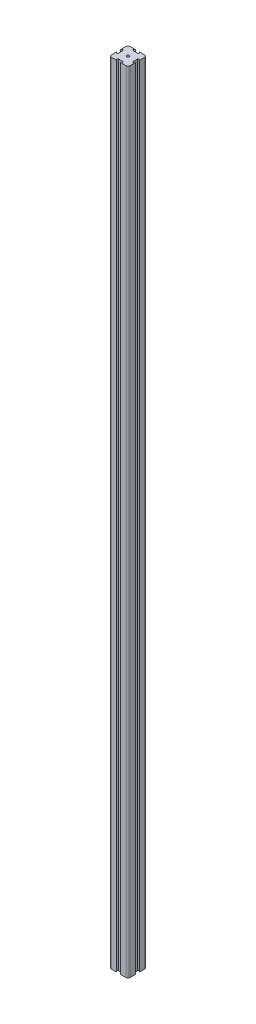
SolidWorks part; units mm, degrees
ref_plane "Front Plane" through (0, 0, 0) normal (0, 0, 1) x (1, 0, 0)
ref_plane "Top Plane" through (0, 0, 0) normal (0, 1, 0) x (1, 0, 0)
ref_plane "Right Plane" through (0, 0, 0) normal (1, 0, 0) x (0, 0, -1)
sketch "Esquisse4" plane through (0, 0, 0) normal (0, 1, 0) x (1, 0, 0)
  line L0 (-17.5, 22.5) -> (-5, 22.5)
  line L1 (22.5, 5) -> (22.5, 17.5)
  line L2 (0, 0) -> (22.5, 0) construction
  line L3 (5, 22.5) -> (17.5, 22.5)
  line L4 (0, 22.5) -> (0, 0) construction
  line L5 (-5, -17.5) -> (5, -17.5)
  line L6 (5, -22.5) -> (17.5, -22.5)
  line L7 (17.5, 5) -> (17.5, -5)
  line L8 (-5, -22.5) -> (-17.5, -22.5)
  line L10 (-5, 20) -> (5, 20) construction
  line L11 (0, 0) -> (0, -28.4326) construction
  line L12 (-5, 17.5) -> (5, 17.5)
  line L13 (17.5, 22.5) -> (17.5, -22.5) construction
  line L14 (-22.5, 17.5) -> (-22.5, 5)
  line L15 (-22.5, -5) -> (-22.5, -17.5)
  line L17 (-17.5, 5) -> (-17.5, -5)
  line L18 (0, 0) -> (-28.2169, 0) construction
  line L19 (22.5, -5) -> (22.5, -17.5)
  arc A0 (17.5, 22.5) -> (22.5, 17.5) centre (17.5, 17.5) cw
  arc A1 (17.5, -22.5) -> (22.5, -17.5) centre (17.5, -17.5) ccw
  arc A2 (-22.5, -17.5) -> (-17.5, -22.5) centre (-17.5, -17.5) ccw
  arc A3 (-17.5, 22.5) -> (-22.5, 17.5) centre (-17.5, 17.5) ccw
  arc A5 (-5, 22.5) -> (-5, 17.5) centre (-5, 20) ccw
  arc A6 (5, 17.5) -> (5, 22.5) centre (5, 20) ccw
  arc A7 (-5, -17.5) -> (-5, -22.5) centre (-5, -20) ccw
  arc A8 (5, -22.5) -> (5, -17.5) centre (5, -20) ccw
  arc A9 (-17.5, -5) -> (-22.5, -5) centre (-20, -5) cw
  arc A10 (22.5, -5) -> (17.5, -5) centre (20, -5) cw
  arc A11 (-17.5, 5) -> (-22.5, 5) centre (-20, 5) ccw
  arc A12 (22.5, 5) -> (17.5, 5) centre (20, 5) ccw
  point P8 (22.5, 22.5)
  point P13 (0, -17.5)
  point P20 (-22.5, 22.5)
  point P23 (0, 20)
  dimension "D4" = 5
  dimension "D6" = 5
  dimension "D7" = 5
  dimension "D8" = 5
  dimension "D20" = 10
  dimension "D24" = 12.5
  dimension "D2" = 22.5
  dimension "D3" = 45
  dimension "D5" = 10
  dimension "D10" = 10
  dimension "D11" = 12.5
  dimension "D12" = 22.5
  dimension "D13" = 5
  dimension "D14" = 17.5
  dimension "D15" = 12.5
  dimension "D16" = 45
  dimension "D17" = 2.5
  dimension "D18" = 5
  dimension "D19" = 45
  dimension "D21" = 5
  dimension "D22" = 17.5
  dimension "D23" = 10
  dimension "D25" = 5
extrude "Boss.-Extru.2" add sketch "Esquisse4" along normal blind 1900 contours L15 A2 L8 A7 L5 A8 L6 A1 L19 A10 L7 A12 L1 A0 L3 A6 L12 A5 L0 A3 L14 A11 L17 A9
sketch "Esquisse5" plane through (0, 0, 0) normal (0, -1, 0) x (1, 0, 0)
  circle A0 centre (0, 0) radius 3
extrude "Enlèv. mat.-Extru.1" cut sketch "Esquisse5" against normal through all
